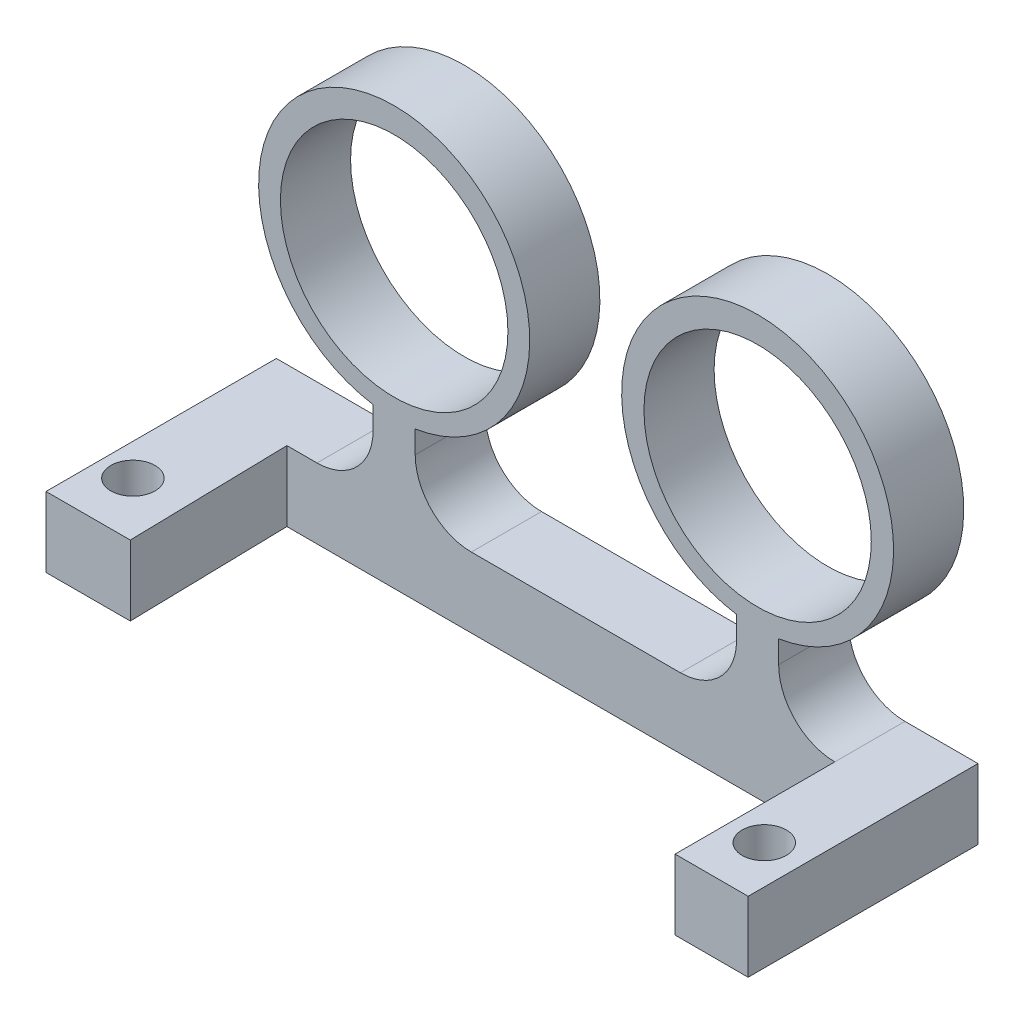
SolidWorks part; units mm, degrees
ref_plane "Alzado" through (0, 0, 0) normal (0, 0, 1) x (1, 0, 0)
ref_plane "Planta" through (0, 0, 0) normal (0, 1, 0) x (1, 0, 0)
ref_plane "Vista lateral" through (0, 0, 0) normal (1, 0, 0) x (0, 0, -1)
sketch "Sketch1" plane through (0, 0, 0) normal (0, 0, 1) x (1, 0, 0)
  line L0 (0, 0) -> (50, 0)
  line L1 (0, 0) -> (0, 5)
  line L2 (50, 0) -> (50, 5)
  line L3 (0, 5) -> (11.8947, 5)
  line L4 (50, 5) -> (40.7947, 5)
  line L5 (13.3947, 19.9091) -> (14.8947, 19.9091) construction
  line L6 (14.8947, 19.9091) -> (11.8947, 19.9091) construction
  line L7 (14.8947, 19.9091) -> (14.8947, 5) construction
  line L8 (14.8947, 5) -> (11.8947, 5) construction
  line L9 (11.8947, 5) -> (11.8947, 19.9091) construction
  line L11 (39.2947, 19.9091) -> (40.7947, 19.9091) construction
  line L13 (40.7947, 19.9091) -> (37.7947, 19.9091) construction
  line L15 (37.7947, 19.9091) -> (37.7947, 5) construction
  line L16 (40.7947, 19.9091) -> (40.7947, 5) construction
  line L17 (37.7947, 5) -> (14.8947, 5)
  line L18 (14.8947, 5) -> (14.8947, 10.6)
  line L19 (11.8947, 5) -> (11.8947, 10.6)
  line L20 (37.7947, 5) -> (37.7947, 10.6)
  line L21 (40.7947, 5) -> (40.7947, 10.6)
  circle A10 centre (13.3947, 19.9091) radius 8.1064
  circle A11 centre (39.2947, 19.9091) radius 8.1
  arc A14 (11.8947, 10.6) -> (14.8947, 10.6) centre (13.3947, 20.1429) cw
  arc A15 (37.7947, 10.6) -> (40.7947, 10.6) centre (39.2947, 20.1716) cw
  dimension "D10" = 5.6
  dimension "D14" = 16.2128
  dimension "D8" = 5.6
  dimension "D15" = 9.6884
  dimension "D5" = 3
  dimension "D12" = 9.66
  dimension "D13" = 16.2128
  dimension "D16" = 16.2
  dimension "D1" = 50
  dimension "D2" = 5
  dimension "D3" = 5
  dimension "D4" = 1.5
  dimension "D6" = 1.5
  dimension "D7" = 3
  dimension "D9" = 5.6
  dimension "D11" = 5.6
extrude "Boss-Extrude2" add sketch "Sketch1" along normal blind 5
sketch "Sketch2" plane through (0, 5, 0) normal (0, 1, 0) x (1, 0, 0)
  circle A0 centre (2.2768, -12.5) radius 1.5754
  circle A1 centre (47.267, -12.5) radius 1.5754
  dimension "D1" = 3.1508
  dimension "D2" = 3.1508
fillet "Fillet1" radius 4 4 edges at (11.8947, 5, 2.5) (14.8947, 5, 2.5) (37.7947, 5, 2.5) (40.7947, 5, 2.5)
sketch "Sketch3" plane through (0, 5, 0) normal (0, 1, 0) x (1, 0, 0)
  line L0 (50, -5) -> (50, 0) construction
  line L1 (5.6428, 0) -> (0, 0)
  line L2 (5.6428, 0) -> (6.0013, -16.4109)
  line L3 (6.0013, -16.4109) -> (0, -16.4162)
  line L4 (0, 0) -> (0, -16.4162)
  line L5 (5.6428, 0) -> (0, -16.4162) construction
  line L6 (6.0013, -16.4109) -> (0, 0) construction
  line L7 (44.7947, 0) -> (50, 0)
  line L8 (44.7947, 0) -> (44.7947, -16.3809)
  line L9 (44.7947, -16.3809) -> (50, -16.3809)
  line L10 (50, 0) -> (50, -16.3809)
  line L11 (44.7947, 0) -> (50, -16.3809) construction
  line L12 (44.7947, -16.3809) -> (50, 0) construction
  line L13 (44.7947, 0) -> (44.7947, -5) construction
  line L14 (0, -5) -> (0, 0) construction
  line L15 (7.8947, 0) -> (0, 0) construction
  point P4 (3.9474, -8.2062)
  point P9 (94.7294, -42.9995)
  point P10 (2.8214, -8.2081)
  dimension "D1" = 3
extrude "Boss-Extrude3" add sketch "Sketch3" against normal up to vertex (5 mm away)
extrude "Cut-Extrude1" cut sketch "Sketch2" against normal up to vertex (5 mm away)
